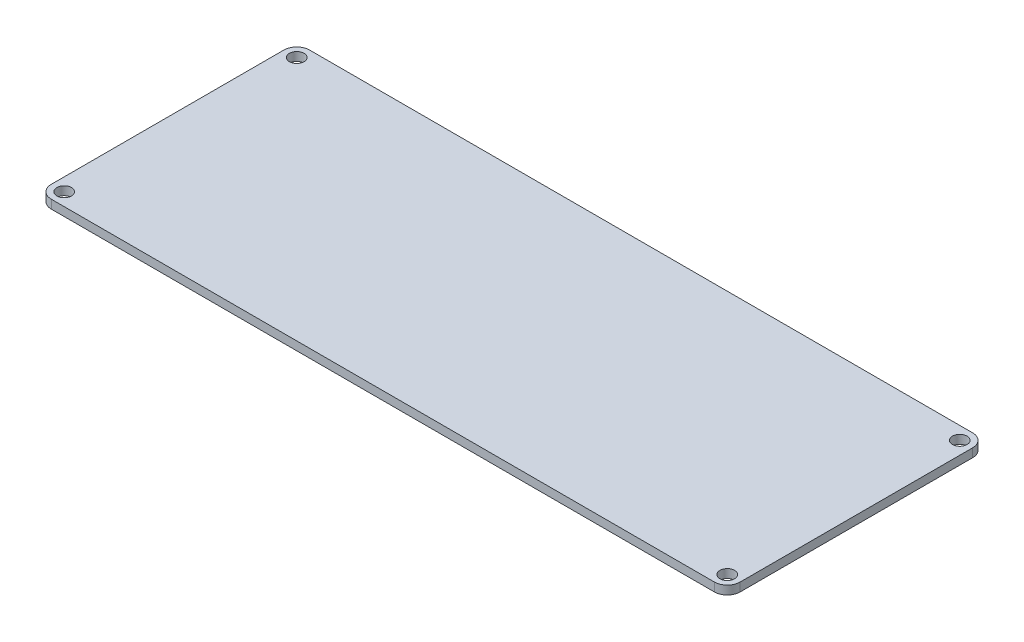
SolidWorks part; units mm, degrees
material "ABS"
ref_plane "Front Plane" through (0, 0, 0) normal (0, 0, 1) x (1, 0, 0)
ref_plane "Top Plane" through (0, 0, 0) normal (0, 1, 0) x (1, 0, 0)
ref_plane "Right Plane" through (0, 0, 0) normal (1, 0, 0) x (0, 0, -1)
sketch "Sketch1" plane through (0, 0, 0) normal (0, 1, 0) x (1, 0, 0)
  line L1 (-80, -30) -> (80, -30)
  line L2 (-80, -30) -> (-80, 30)
  line L3 (-80, 30) -> (80, 30)
  line L4 (80, -30) -> (80, 30)
  line L5 (-80, -30) -> (80, 30) construction
  line L6 (-80, 30) -> (80, -30) construction
  point P0 (0, 0)
  dimension "D1" = 160
  dimension "D2" = 60
extrude "Boss-Extrude1" add sketch "Sketch1" along normal blind 2
fillet "Fillet1" radius 3 4 edges at (80, 1, -30) (-80, 1, -30) (80, 1, 30) (-80, 1, 30)
hole_wizard "M3 Clearance Hole1" positions "Sketch3" profile "Sketch2" hole size "M3" standard "ANSI Metric"
sketch "Sketch3" plane through (0, 2, 0) normal (0, 1, 0) x (1, 0, 0)
  point P0 (-77, 27)
  point P3 (-77, -27)
  point P6 (77, 27)
  point P9 (77, -27)
sketch "Sketch2" plane through (-77, 2, -27) normal (1, 0, 0) x (0, 0, 1)
  line L0 (0, 0) -> (0, 10)
  line L1 (0, 10) -> (1.7, 10)
  line L2 (1.7, 10) -> (1.7, 0)
  line L5 (1.7, 0) -> (0, 0)
  line L10 (0, 10) -> (-1.7, 10) construction
  line L11 (0, -6.35) -> (0, 107.95) construction
  dimension "Hole Dia." = 3.4
  dimension "Hole Depth" = 10
  dimension "Drill Angle" = 180
